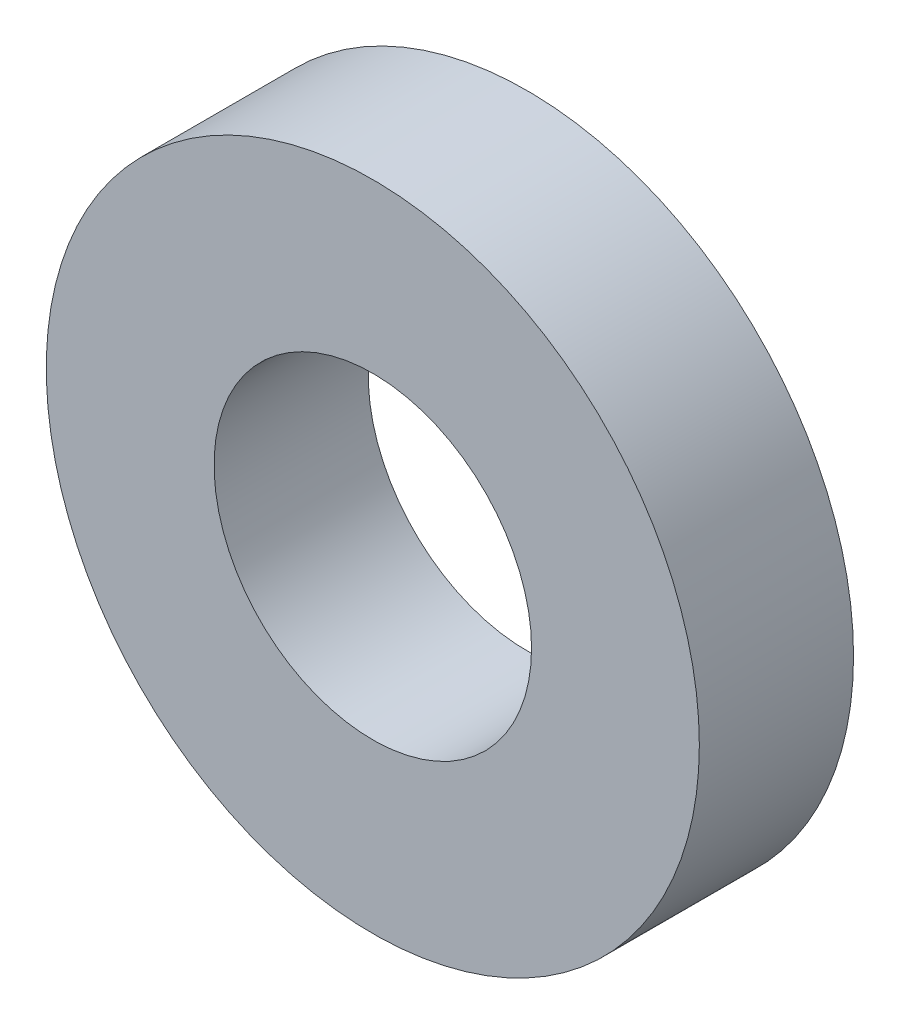
SolidWorks part; units mm, degrees
ref_plane "Front Plane" through (0, 0, 0) normal (0, 0, 1) x (1, 0, 0)
ref_plane "Top Plane" through (0, 0, 0) normal (0, 1, 0) x (1, 0, 0)
ref_plane "Right Plane" through (0, 0, 0) normal (1, 0, 0) x (0, 0, -1)
sketch "Sketch1" plane through (0, 0, 0) normal (0, 0, 1) x (1, 0, 0)
  circle A0 centre (0, 0) radius 36
  circle A1 centre (0, 0) radius 17.5
  dimension "D1" = 35
  dimension "D2" = 72
extrude "Boss-Extrude1" add sketch "Sketch1" along normal mid plane 17
